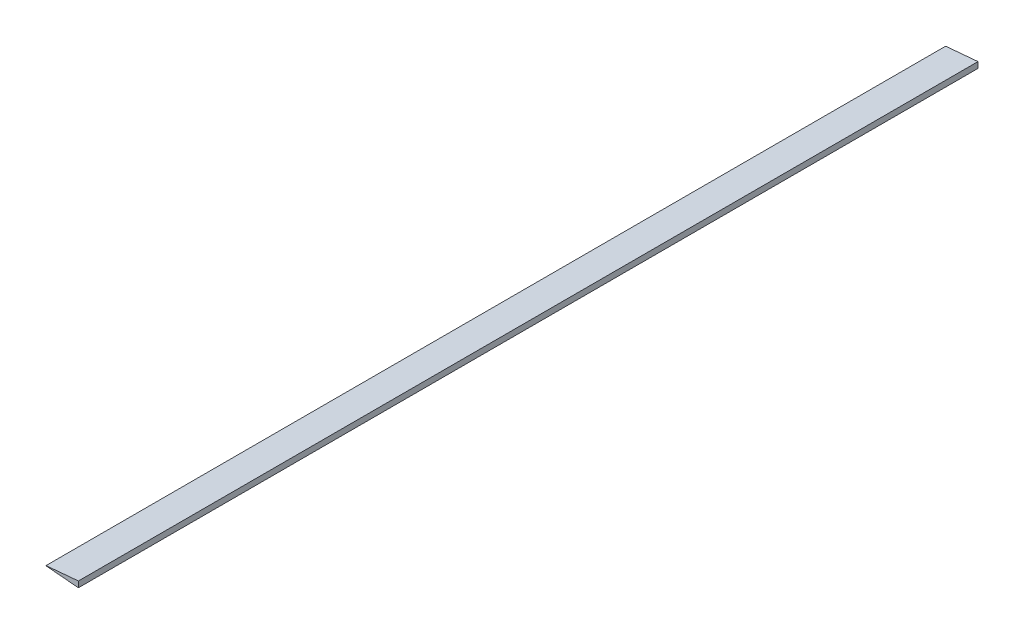
SolidWorks part; units mm, degrees
ref_plane "Front Plane" through (0, 0, 0) normal (0, 0, 1) x (1, 0, 0)
ref_plane "Top Plane" through (0, 0, 0) normal (0, 1, 0) x (1, 0, 0)
ref_plane "Right Plane" through (0, 0, 0) normal (1, 0, 0) x (0, 0, -1)
sketch "Sketch1" plane through (0, 0, 0) normal (0, 0, 1) x (1, 0, 0)
  line L0 (-71.0668, 2.789) -> (-71.0668, -2.789)
  line L1 (-101.524, 0.0959) -> (-101.524, -0.0959)
  spline S0 degree 3 poles (-71.0668, 2.789) (-71.1808, 2.7809) (-72.8734, 2.6615) (-76.051, 2.4154) (-80.491, 2.0609) (-84.605, 1.7129) (-88.3483, 1.382) (-91.6798, 1.0752) (-94.563, 0.8001) (-96.9663, 0.5635) (-98.8634, 0.372) (-100.2335, 0.2309) (-101.0616, 0.1446) (-101.4313, 0.1057) (-101.524, 0.0959) knots 0 0 0 0 0.011212 0.166483 0.312686 0.448211 0.571563 0.681381 0.776452 0.855723 0.918312 0.963525 0.990856 1 1 1 1
  spline S1 degree 3 poles (-71.0668, -2.789) (-71.1808, -2.7809) (-72.8734, -2.6615) (-76.051, -2.4154) (-80.491, -2.0609) (-84.605, -1.7129) (-88.3483, -1.382) (-91.6798, -1.0752) (-94.563, -0.8001) (-96.9663, -0.5635) (-98.8634, -0.372) (-100.2335, -0.2309) (-101.0616, -0.1446) (-101.4313, -0.1057) (-101.524, -0.0959) knots 0 0 0 0 0.011212 0.166483 0.312686 0.448211 0.571563 0.681381 0.776452 0.855723 0.918312 0.963525 0.990856 1 1 1 1
extrude "Boss-Extrude1" add sketch "Sketch1" along normal mid plane 845.8
